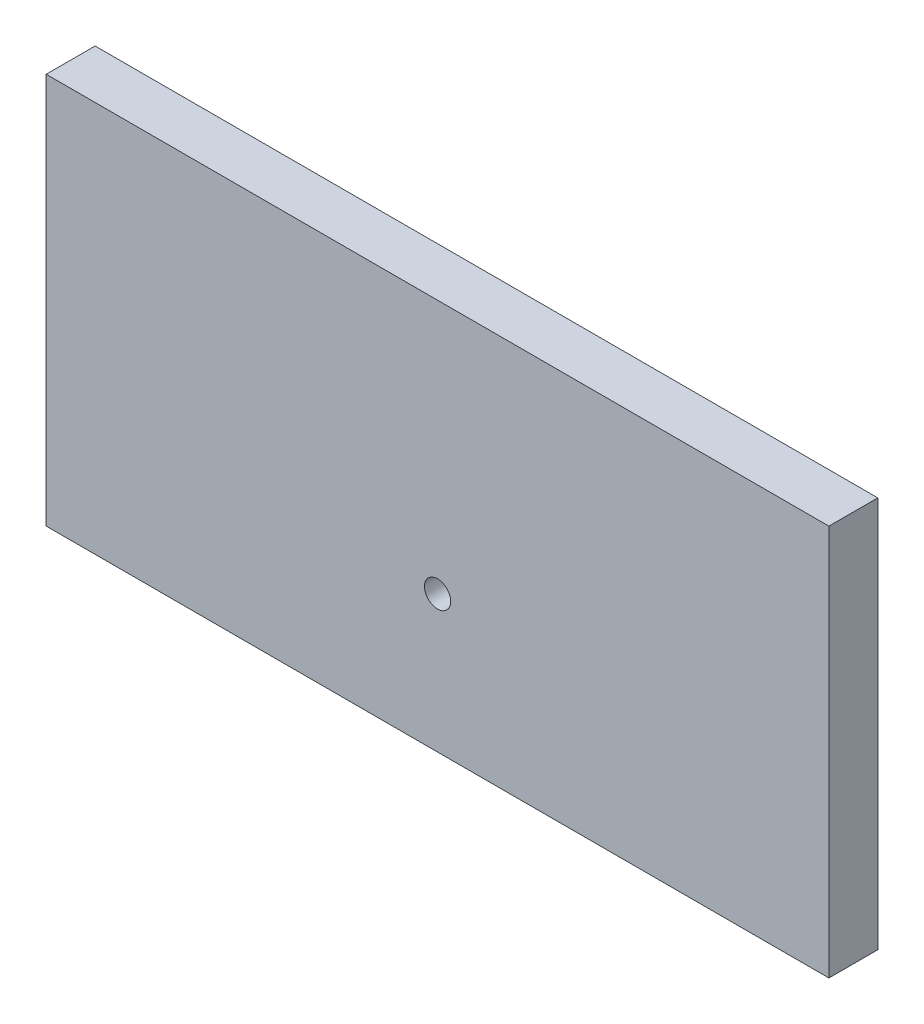
SolidWorks part; units mm, degrees
material "6061 Alloy"
ref_plane "Front Plane" through (0, 0, 0) normal (0, 0, 1) x (1, 0, 0)
ref_plane "Top Plane" through (0, 0, 0) normal (0, 1, 0) x (1, 0, 0)
ref_plane "Right Plane" through (0, 0, 0) normal (1, 0, 0) x (0, 0, -1)
sketch "Sketch2" plane through (0, 0, 0) normal (0, 1, 0) x (1, 0, 0)
  line L1 (0, 0) -> (101.6, 0)
  line L2 (0, 0) -> (0, 6.35)
  line L3 (0, 6.35) -> (101.6, 6.35)
  line L4 (101.6, 0) -> (101.6, 6.35)
  dimension "D1" = 6.35
  dimension "D2" = 101.6
extrude "Boss-Extrude1" add sketch "Sketch2" along normal blind 50.8
sketch "Sketch3" plane through (0, 0, 0) normal (0, 0, 1) x (1, 0, 0)
  line L0 (50.8, 0) -> (50.8, 50000) construction
  line L1 (0, 0) -> (101.6, 0) construction
  point P0 (50.8, 17.78)
  point P5 (50.8, 0)
  point P6 (50.8, 21.3325)
  dimension "D1" = 17.78
hole_wizard "M3 Clearance Hole1" positions "Sketch4" profile "Sketch6" hole size "M3" standard "ANSI Metric" end condition up to next
sketch "Sketch4" plane through (0, 0, 0) normal (0, 0, 1) x (1, 0, 0)
  point P0 (50.8, 17.78)
sketch "Sketch6" plane through (50.8, 17.78, 0) normal (1, 0, 0) x (0, -1, 0)
  line L0 (0, 0) -> (0, 6.35)
  line L1 (0, 6.35) -> (1.7, 6.35)
  line L2 (1.7, 6.35) -> (1.7, 0)
  line L5 (1.7, 0) -> (0, 0)
  line L11 (0, -6.35) -> (0, 107.95) construction
  dimension "Thru Hole Dia." = 3.4
  dimension "Thru Hole Depth" = 6.35
